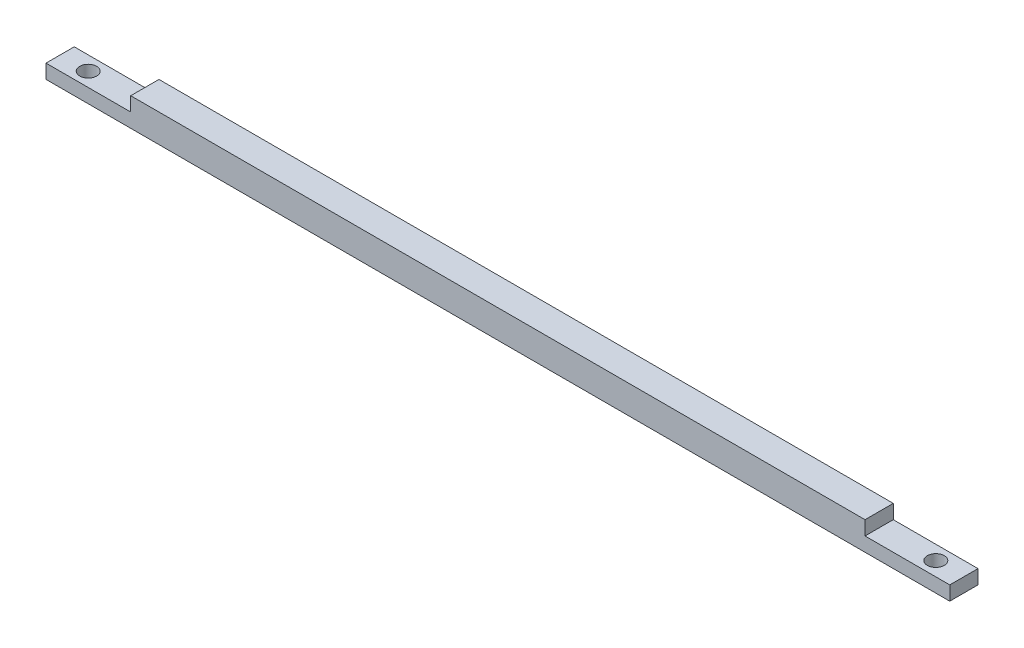
SolidWorks part; units mm, degrees
ref_plane "Front Plane" through (0, 0, 0) normal (0, 0, 1) x (1, 0, 0)
ref_plane "Top Plane" through (0, 0, 0) normal (0, 1, 0) x (1, 0, 0)
ref_plane "Right Plane" through (0, 0, 0) normal (1, 0, 0) x (0, 0, -1)
sketch "Sketch1" plane through (0, 0, 0) normal (0, 0, 1) x (1, 0, 0)
  line L1 (-80, 2.5) -> (80, 2.5)
  line L2 (-80, 2.5) -> (-80, -2.5)
  line L3 (-80, -2.5) -> (80, -2.5)
  line L4 (80, 2.5) -> (80, -2.5)
  line L5 (-80, 2.5) -> (80, -2.5) construction
  line L6 (-80, -2.5) -> (80, 2.5) construction
  point P0 (0, 0)
  dimension "D1" = 160
  dimension "D2" = 5
extrude "Boss-Extrude1" add sketch "Sketch1" along normal blind 5
sketch "Sketch2" plane through (0, 2.5, 0) normal (0, 1, 0) x (1, 0, 0)
  line L0 (80, -5) -> (-80, -5) construction
  line L1 (-80, 0) -> (-65, 0)
  line L2 (-80, 0) -> (-80, -5)
  line L3 (-80, -5) -> (-65, -5)
  line L4 (-65, 0) -> (-65, -5)
  line L5 (0, 0) -> (0, -25.4944) construction
  line L6 (80, -5) -> (65, -5)
  line L7 (65, 0) -> (65, -5)
  line L8 (80, 0) -> (65, 0)
  line L9 (80, 0) -> (80, -5)
  dimension "D1" = 15
extrude "Cut-Extrude1" cut sketch "Sketch2" against normal blind 2.5
sketch "Sketch3" plane through (0, 0, 0) normal (0, 1, 0) x (1, 0, 0)
  line L0 (-75, 0) -> (-75, -5) construction
  line L3 (-65, -5) -> (-65, 0) construction
  line L4 (0, 0) -> (0, -5.063) construction
  line L5 (75, 0) -> (75, -5) construction
  line L6 (-80, -2.5) -> (-60, -2.5) construction
  circle A0 centre (-75.0309, -2.4999) radius 1.5
  circle A1 centre (75.0309, -2.4999) radius 1.5
  dimension "D2" = 1.5
  dimension "D1" = 10
extrude "Cut-Extrude2" cut sketch "Sketch3" against normal blind 2.5
